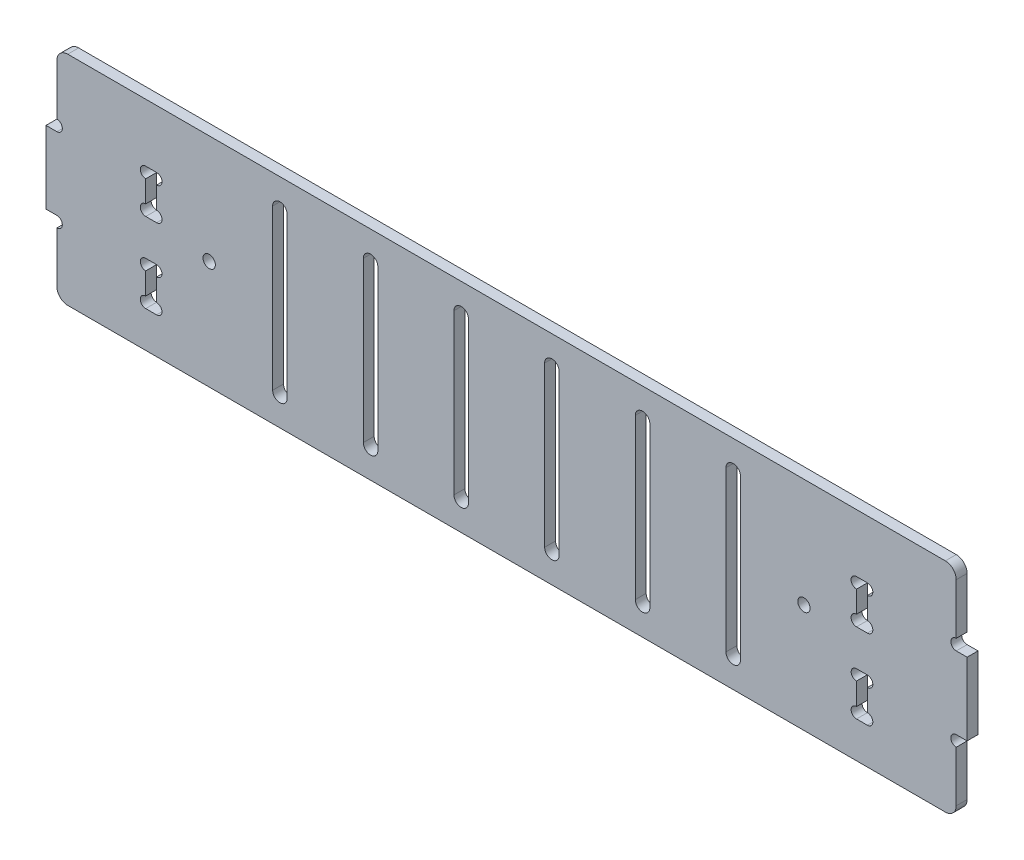
SolidWorks part; units mm, degrees
ref_plane "前视基准面" through (0, 0, 0) normal (0, 0, 1) x (1, 0, 0)
ref_plane "上视基准面" through (0, 0, 0) normal (0, 1, 0) x (1, 0, 0)
ref_plane "右视基准面" through (0, 0, 0) normal (1, 0, 0) x (0, 0, -1)
sketch "草图1" plane through (0, 0, 0) normal (0, 0, 1) x (1, 0, 0)
  line L1 (-127, 27.5) -> (127, 27.5)
  line L2 (-127, 27.5) -> (-127, -27.5)
  line L3 (-127, -27.5) -> (127, -27.5)
  line L4 (127, 27.5) -> (127, -27.5)
  line L5 (-127, 27.5) -> (127, -27.5) construction
  line L6 (-127, -27.5) -> (127, 27.5) construction
  point P0 (0, 0)
  dimension "D1" = 55
  dimension "D2" = 254
extrude "凸台-拉伸1" add sketch "草图1" along normal blind 3
sketch "草图2" plane through (0, 0, 3) normal (0, 0, 1) x (1, 0, 0)
  line L0 (0, -27.5) -> (0, 27.5) construction
  line L2 (-127, -27.5) -> (-124, -27.5)
  line L4 (-127, -27.5) -> (-127, -7.5)
  line L5 (-127, -7.5) -> (-124, -7.5)
  line L6 (-124, -27.5) -> (-124, -7.5)
  line L7 (-127, 27.5) -> (-124, 27.5)
  line L8 (-127, 27.5) -> (-127, 12.5)
  line L9 (-127, 12.5) -> (-124, 12.5)
  line L10 (-124, 27.5) -> (-124, 12.5)
  line L11 (-127, -27.5) -> (127, -27.5) construction
  line L12 (127, 27.5) -> (-127, 27.5) construction
  line L13 (127, -7.5) -> (124, -7.5)
  line L14 (124, -27.5) -> (124, -7.5)
  line L15 (127, -27.5) -> (124, -27.5)
  line L16 (127, -27.5) -> (127, -7.5)
  line L17 (127, 12.5) -> (124, 12.5)
  line L18 (124, 27.5) -> (124, 12.5)
  line L19 (127, 27.5) -> (124, 27.5)
  line L20 (127, 27.5) -> (127, 12.5)
  dimension "D1" = 20
  dimension "D2" = 20
  dimension "D3" = 3
extrude "切除-拉伸1" cut sketch "草图2" against normal through all
sketch "草图3" plane through (0, 0, 3) normal (0, 0, 1) x (1, 0, 0)
  line L0 (-124, -27.5) -> (-124, -7.5) construction
  line L1 (-99.5, -17.5) -> (-96.5, -17.5)
  line L2 (-99.5, -17.5) -> (-99.5, -5.5)
  line L3 (-99.5, -5.5) -> (-96.5, -5.5)
  line L4 (-96.5, -17.5) -> (-96.5, -5.5)
  line L5 (-99.5, 16.5) -> (-96.5, 16.5)
  line L6 (-99.5, 16.5) -> (-99.5, 4.5)
  line L7 (-99.5, 4.5) -> (-96.5, 4.5)
  line L8 (-96.5, 16.5) -> (-96.5, 4.5)
  line L9 (-124, -27.5) -> (124, -27.5) construction
  line L10 (0, -1.65) -> (0, 1.65) construction
  line L11 (99.5, -5.5) -> (96.5, -5.5)
  line L12 (96.5, -17.5) -> (96.5, -5.5)
  line L13 (99.5, -17.5) -> (96.5, -17.5)
  line L14 (99.5, -17.5) -> (99.5, -5.5)
  line L15 (99.5, 4.5) -> (96.5, 4.5)
  line L16 (96.5, 16.5) -> (96.5, 4.5)
  line L17 (99.5, 16.5) -> (96.5, 16.5)
  line L18 (99.5, 16.5) -> (99.5, 4.5)
  dimension "D1" = 24.5
  dimension "D2" = 10
  dimension "D3" = 12
  dimension "D4" = 12
  dimension "D5" = 10
  dimension "D6" = 3
extrude "切除-拉伸2" cut sketch "草图3" against normal through all
sketch "草图4" plane through (0, 0, 3) normal (0, 0, 1) x (1, 0, 0)
  line L0 (-96.5, 4.5) -> (-96.5, 16.5) construction
  line L1 (-99.5, 16.5) -> (-99.5, 4.5) construction
  line L2 (-96.5, 16.5) -> (-99.5, 16.5) construction
  line L3 (-96.5, 10.5) -> (-99.5, 10.5) construction
  line L4 (-96.5, -11.5) -> (-99.5, -11.5) construction
  line L5 (-96.5, -17.5) -> (-96.5, -5.5) construction
  line L6 (-99.5, -5.5) -> (-99.5, -17.5) construction
  line L7 (-96.5, -5.5) -> (-99.5, -5.5) construction
  line L8 (0, -1.65) -> (0, 1.65) construction
  line L9 (96.5, -11.5) -> (99.5, -11.5) construction
  line L10 (96.5, 10.5) -> (99.5, 10.5) construction
  circle A2 centre (-96.5, 15) radius 1.5
  circle A3 centre (-99.5, 15) radius 1.5
  circle A4 centre (-99.5, 6) radius 1.5
  circle A5 centre (-96.5, 6) radius 1.5
  circle A6 centre (-96.5, -6.975) radius 1.475
  circle A7 centre (-99.5, -7) radius 1.5
  circle A8 centre (-99.5, -16) radius 1.5
  circle A9 centre (-96.5, -16.025) radius 1.475
  circle A10 centre (96.5, -16.025) radius 1.475
  circle A11 centre (99.5, -16) radius 1.5
  circle A12 centre (99.5, -7) radius 1.5
  circle A13 centre (96.5, -6.975) radius 1.475
  circle A14 centre (96.5, 6) radius 1.5
  circle A15 centre (99.5, 6) radius 1.5
  circle A16 centre (99.5, 15) radius 1.5
  circle A17 centre (96.5, 15) radius 1.5
  line M8 (-99.5, 4.5) -> (-99.5, 16.5)
  line M10 (-96.5, 16.5) -> (-96.5, 4.5)
  line M12 (99.5, -5.5) -> (99.5, -17.5)
  line M14 (96.5, -17.5) -> (96.5, -5.5)
  line M16 (99.5, 16.5) -> (99.5, 4.5)
  line M18 (96.5, 4.5) -> (96.5, 16.5)
  line M20 (-99.5, -17.5) -> (-99.5, -5.5)
  line M22 (-96.5, -5.5) -> (-96.5, -17.5)
  dimension "D1" = 3
  dimension "D2" = 3
  dimension "D3" = 2.95
  dimension "D4" = 3
extrude "切除-拉伸3" cut sketch "草图4" against normal through all contours A11 M12 | A10 M14 | A13 M14 | A12 M12 | A15 M16 | A14 M18 | A17 M18 | A16 M16 | A2 M10 | A3 M8 | A4 M8 | A5 M10 | A6 M22 | A7 M20 | A8 M20 | A9 M22
sketch "草图5" plane through (0, 0, 3) normal (0, 0, 1) x (1, 0, 0)
  line L0 (-124, 12.5) -> (-124, 27.5) construction
  line L1 (-124, -27.5) -> (-124, -7.5) construction
  line L2 (-127, 12.5) -> (-124, 12.5) construction
  line L3 (-124, -7.5) -> (-127, -7.5) construction
  line L4 (0, -1.65) -> (0, 1.65) construction
  circle A0 centre (-124, 14) radius 1.5
  circle A1 centre (-124, -9) radius 1.5
  circle A2 centre (124, -9) radius 1.5
  circle A3 centre (124, 14) radius 1.5
  dimension "D1" = 3
  dimension "D2" = 3
extrude "切除-拉伸4" cut sketch "草图5" against normal through all
sketch "草图6" plane through (0, 0, 3) normal (0, 0, 1) x (1, 0, 0)
  line L0 (-124, -27.5) -> (124, -27.5) construction
  line L2 (-127, 12.5) -> (-127, -7.5) construction
  line L3 (0, -1.65) -> (0, 1.65) construction
  circle A0 centre (-82, 2.5) radius 1.7
  circle A1 centre (82, 2.5) radius 1.7
  dimension "D1" = 3.4
  dimension "D2" = 30
  dimension "D3" = 45
extrude "切除-拉伸5" cut sketch "草图6" against normal through all
sketch "草图7" plane through (0, 27.5, 0) normal (0, 1, 0) x (1, 0, 0)
  line L4 (124, 0) -> (-124, 0)
  line L5 (-124, 0) -> (-124, -3)
  line L6 (-124, -3) -> (124, -3)
  line L7 (124, -3) -> (124, 0)
  line L8 (124, 0) -> (-124, 0)
  line L9 (-124, 0) -> (-124, -3)
  line L10 (-124, -3) -> (124, -3)
  line L11 (124, -3) -> (124, 0)
  dimension "D1" = 0
extrude "凸台-拉伸2" add sketch "草图7" along normal blind 5
sketch "草图8" plane through (0, 0, 3) normal (0, 0, 1) x (1, 0, 0)
  line L0 (0, -27.5) -> (0, 32.5) construction
  line L1 (62.5, 24.5) -> (62.5, -19.5) construction
  line L2 (-124, -27.5) -> (124, -27.5) construction
  line L3 (-124, 32.5) -> (124, 32.5) construction
  line L4 (-127, 2.5) -> (0, 2.5) construction
  line L5 (-127, 12.5) -> (-127, -7.5) construction
  line L6 (-62.5, 24.5) -> (-62.5, -19.5) construction
  line L7 (-60.5, 24.5) -> (-60.5, -19.5)
  line L8 (-64.5, 24.5) -> (-64.5, -19.5)
  line L9 (-39.5, 24.5) -> (-39.5, -19.5)
  line L10 (-35.5, 24.5) -> (-35.5, -19.5)
  line L11 (-37.5, 24.5) -> (-37.5, -19.5) construction
  line L12 (-14.5, 24.5) -> (-14.5, -19.5)
  line L13 (-10.5, 24.5) -> (-10.5, -19.5)
  line L14 (-12.5, 24.5) -> (-12.5, -19.5) construction
  line L15 (60.5, 24.5) -> (60.5, -19.5)
  line L16 (64.5, 24.5) -> (64.5, -19.5)
  line L17 (37.5, 24.5) -> (37.5, -19.5) construction
  line L18 (35.5, 24.5) -> (35.5, -19.5)
  line L19 (39.5, 24.5) -> (39.5, -19.5)
  line L20 (12.5, 24.5) -> (12.5, -19.5) construction
  line L21 (10.5, 24.5) -> (10.5, -19.5)
  line L22 (14.5, 24.5) -> (14.5, -19.5)
  arc A0 (-60.5, 24.5) -> (-64.5, 24.5) centre (-62.5, 24.5) ccw
  arc A1 (-64.5, -19.5) -> (-60.5, -19.5) centre (-62.5, -19.5) ccw
  arc A2 (-35.5, 24.5) -> (-39.5, 24.5) centre (-37.5, 24.5) ccw
  arc A3 (-39.5, -19.5) -> (-35.5, -19.5) centre (-37.5, -19.5) ccw
  arc A4 (-10.5, 24.5) -> (-14.5, 24.5) centre (-12.5, 24.5) ccw
  arc A5 (-14.5, -19.5) -> (-10.5, -19.5) centre (-12.5, -19.5) ccw
  arc A6 (60.5, 24.5) -> (64.5, 24.5) centre (62.5, 24.5) cw
  arc A7 (64.5, -19.5) -> (60.5, -19.5) centre (62.5, -19.5) cw
  arc A8 (35.5, 24.5) -> (39.5, 24.5) centre (37.5, 24.5) cw
  arc A9 (39.5, -19.5) -> (35.5, -19.5) centre (37.5, -19.5) cw
  arc A10 (10.5, 24.5) -> (14.5, 24.5) centre (12.5, 24.5) cw
  arc A11 (14.5, -19.5) -> (10.5, -19.5) centre (12.5, -19.5) cw
  point P13 (-62.5, 2.5)
  point P19 (62.5, 2.5)
  point P22 (-37.5, 2.5)
  point P29 (-12.5, 2.5)
  point P40 (37.5, 2.5)
  point P47 (12.5, 2.5)
  dimension "D1" = 2
  dimension "D5" = 25
  dimension "D2" = 44
  dimension "D3" = 64.5
  dimension "D4" = 3
extrude "切除-拉伸6" cut sketch "草图8" against normal through all
fillet "圆角1" radius 3 4 edges at (124, -27.5, 1.5) (-124, -27.5, 1.5) (124, 32.5, 1.5) (-124, 32.5, 1.5)
